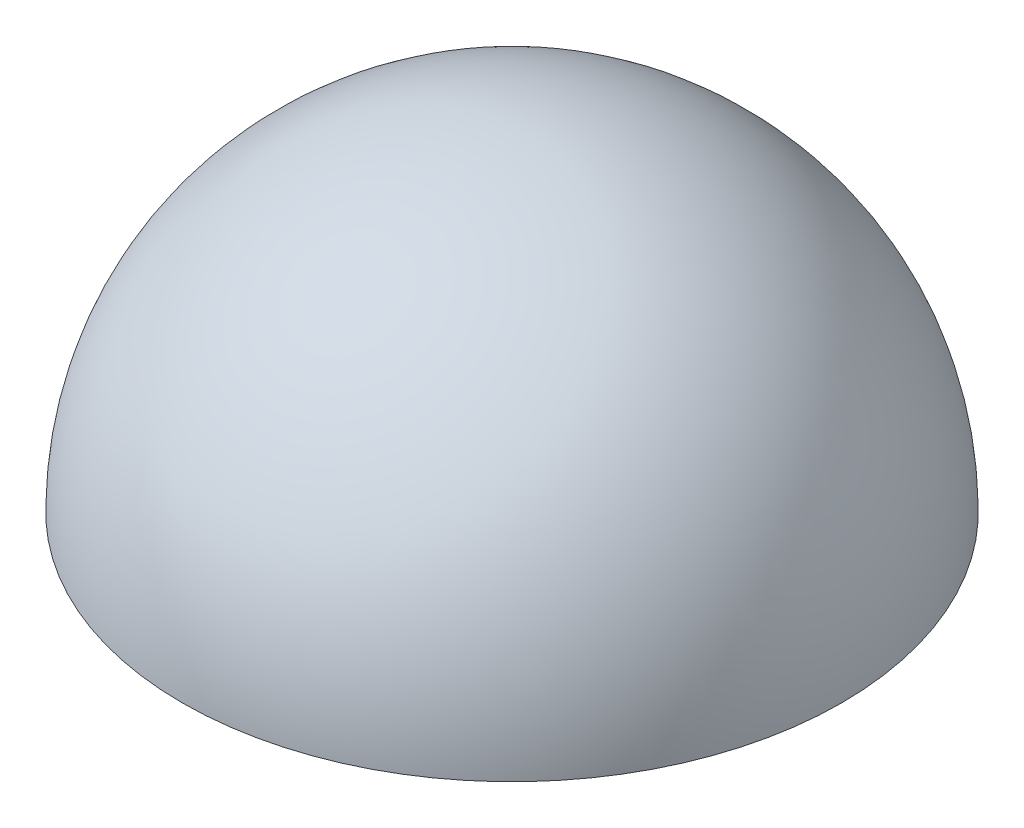
SolidWorks part; units mm, degrees
material "Glass"
ref_plane "Front Plane" through (0, 0, 0) normal (0, 0, 1) x (1, 0, 0)
ref_plane "Top Plane" through (0, 0, 0) normal (0, 1, 0) x (1, 0, 0)
ref_plane "Right Plane" through (0, 0, 0) normal (1, 0, 0) x (0, 0, -1)
sketch "Sketch1" plane through (0, 0, 0) normal (0, 0, 1) x (1, 0, 0)
  line L0 (0, 29.4625) -> (0, -34.1782) construction
  line L1 (-41.5825, 0) -> (63.5599, 0) construction
  line L2 (0, 29) -> (0, 25)
  line L3 (25, 0) -> (29, 0)
  arc A0 (25, 0) -> (0, 25) centre (0, 0) ccw
  arc A1 (29, 0) -> (0, 29) centre (0, 0) ccw
  dimension "D1" = 25
  dimension "D2" = 4
revolve "Revolve1" add sketch "Sketch1" angle 360 about L0
